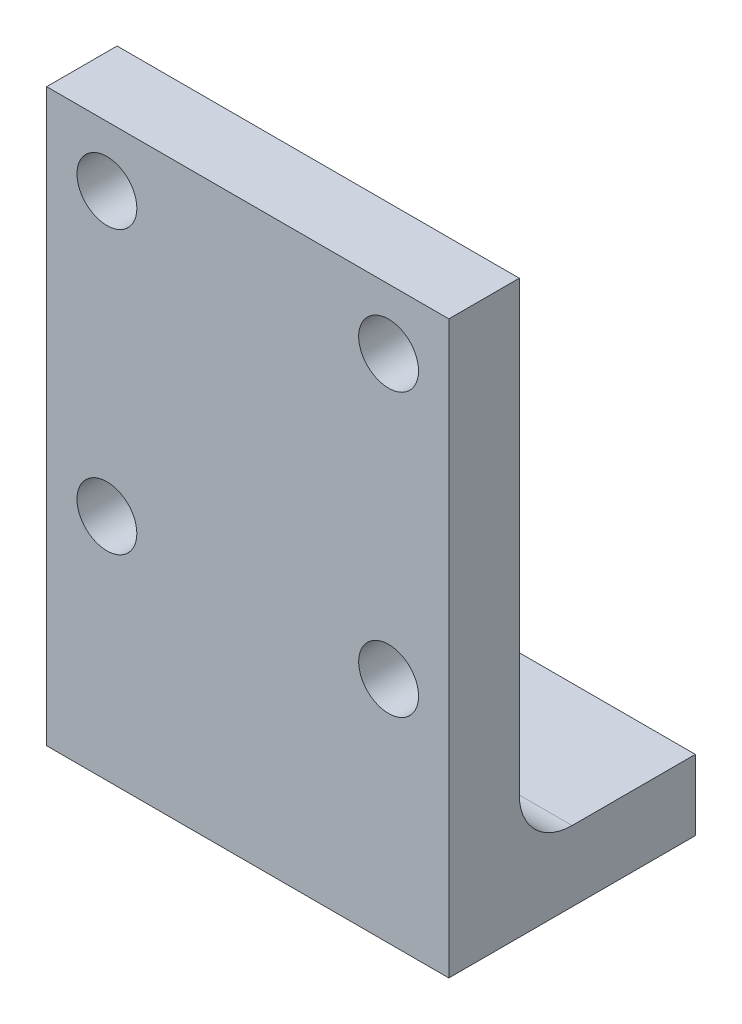
SolidWorks part; units mm, degrees
ref_plane "Front Plane" through (0, 0, 0) normal (0, 0, 1) x (1, 0, 0)
ref_plane "Top Plane" through (0, 0, 0) normal (0, 1, 0) x (1, 0, 0)
ref_plane "Right Plane" through (0, 0, 0) normal (1, 0, 0) x (0, 0, -1)
sketch "Sketch1" plane through (0, 0, 0) normal (0, 0, 1) x (1, 0, 0)
  line L1 (-11.4219, 11.4219) -> (11.4219, 11.4219)
  line L2 (-11.4219, 11.4219) -> (-11.4219, -11.4219)
  line L3 (-11.4219, -11.4219) -> (11.4219, -11.4219)
  line L4 (11.4219, 11.4219) -> (11.4219, -11.4219)
  line L5 (-11.4219, 11.4219) -> (11.4219, -11.4219) construction
  line L6 (-11.4219, -11.4219) -> (11.4219, 11.4219) construction
  circle A0 centre (-8, 8) radius 1.7
  circle A1 centre (8, 8) radius 1.7
  circle A2 centre (8, -8) radius 1.7
  circle A3 centre (-8, -8) radius 1.7
  point P0 (0, 0)
  point P14 (0, 0)
  point P15 (0, 0)
  point P16 (0, 0)
  dimension "D1" = 3.4
  dimension "D2" = 16
  dimension "D3" = 16
extrude "Boss-Extrude1" add sketch "Sketch1" along normal blind 4
sketch "Sketch2" plane through (0, 0, 0) normal (0, 0, 1) x (1, 0, 0)
  line L0 (-11.4219, -11.4219) -> (-11.4219, -21)
  line L1 (-11.4219, -21) -> (11.4219, -21)
  line L2 (11.4219, -21) -> (11.4219, -11.4219)
  line L3 (-11.4219, -11.4219) -> (11.4219, -11.4219) construction
  line L4 (11.4219, -11.4219) -> (-11.4219, -11.4219)
  line L5 (11.4219, -11.4219) -> (11.4219, 11.4219) construction
  circle A0 centre (-8, -8) radius 1.7 construction
  dimension "D1" = 13
extrude "Boss-Extrude2" add sketch "Sketch2" along normal up to vertex (4 mm away)
sketch "Sketch3" plane through (0, 0, 0) normal (0, 0, -1) x (-1, 0, 0)
  line L0 (11.4219, 11.4219) -> (11.4219, -21) construction
  line L1 (-11.4219, -21) -> (11.4219, -21)
  line L2 (-11.4219, -21) -> (-11.4219, -17)
  line L3 (-11.4219, -17) -> (11.4219, -17)
  line L4 (11.4219, -21) -> (11.4219, -17)
  dimension "D1" = 4
extrude "Boss-Extrude3" add sketch "Sketch3" along normal blind 10
fillet "Fillet1" radius 3 1 edges at (0, -17, 0)
equation "\"padding\"=3"
